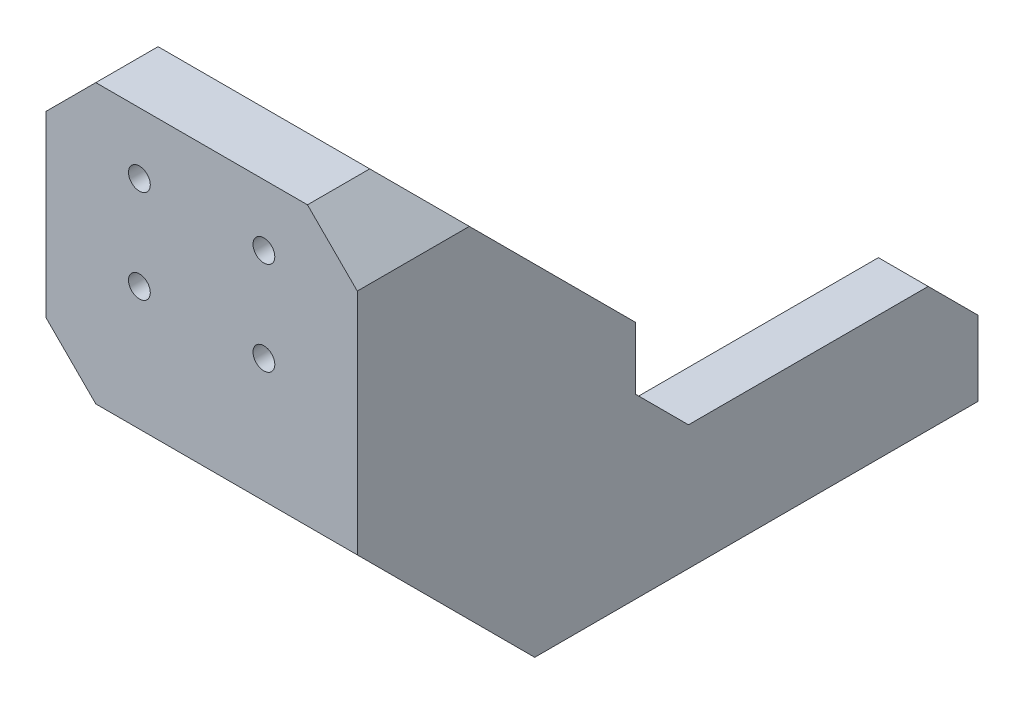
SolidWorks part; units mm, degrees
ref_plane "Front Plane" through (0, 0, 0) normal (0, 0, 1) x (1, 0, 0)
ref_plane "Top Plane" through (0, 0, 0) normal (0, 1, 0) x (1, 0, 0)
ref_plane "Right Plane" through (0, 0, 0) normal (1, 0, 0) x (0, 0, -1)
sketch "Sketch1" plane through (0, 0, 0) normal (0, 1, 0) x (1, 0, 0)
  line L1 (-25, -17.35) -> (25, -17.35)
  line L2 (-25, -17.35) -> (-25, 17.35)
  line L3 (-25, 17.35) -> (25, 17.35)
  line L4 (25, -17.35) -> (25, 17.35)
  line L5 (-25, -17.35) -> (25, 17.35) construction
  line L6 (-25, 17.35) -> (25, -17.35) construction
  point P0 (0, 0)
  dimension "D1" = 50
  dimension "D2" = 34.7
extrude "Boss-Extrude1" add sketch "Sketch1" along normal blind 10
sketch "Sketch2" plane through (0, 10, 0) normal (0, 1, 0) x (1, 0, 0)
  line L1 (-10, -7.5) -> (10, -7.5) construction
  line L2 (-10, -7.5) -> (-10, 7.5) construction
  line L3 (-10, 7.5) -> (10, 7.5) construction
  line L4 (10, -7.5) -> (10, 7.5) construction
  line L5 (-10, -7.5) -> (10, 7.5) construction
  line L6 (-10, 7.5) -> (10, -7.5) construction
  circle A0 centre (-10, 7.5) radius 1.75
  circle A1 centre (10, 7.5) radius 1.75
  circle A2 centre (10, -7.5) radius 1.75
  circle A3 centre (-10, -7.5) radius 1.75
  point P0 (0, 0)
  dimension "D1" = 3.5
  dimension "D2" = 20
  dimension "D3" = 15
extrude "Cut-Extrude1" cut sketch "Sketch2" against normal up to next
sketch "Sketch3" plane through (0, 10, 0) normal (0, 1, 0) x (1, 0, 0)
  circle A3 centre (-10, 7.5) radius 3
  circle A4 centre (10, 7.5) radius 3
  circle A5 centre (10, -7.5) radius 3
  circle A6 centre (-10, -7.5) radius 3
  dimension "D1" = 6
extrude "Cut-Extrude2" cut sketch "Sketch3" against normal blind 5
sketch "Sketch6" plane through (0, 0, 0) normal (0, -1, 0) x (1, 0, 0)
  line L0 (25, 17.35) -> (25, -17.35) construction
  line L1 (-25, 17.35) -> (25, 17.35)
  line L2 (-25, 17.35) -> (-25, 27.35)
  line L3 (-25, 27.35) -> (25, 27.35)
  line L4 (25, 17.35) -> (25, 27.35)
  dimension "D1" = 10
extrude "Boss-Extrude3" add sketch "Sketch6" against normal blind 44.7
sketch "Sketch8" plane through (25, 0, 0) normal (1, 0, 0) x (0, 0, -1)
  line L0 (-27.35, 0) -> (17.35, 0)
  line L1 (-27.35, 0) -> (17.35, 0) construction
  line L2 (17.35, 0) -> (25.85, -8.5)
  line L3 (25.85, -8.5) -> (72.35, -8.5)
  line L4 (72.35, -8.5) -> (72.35, -28.5)
  line L5 (72.35, -28.5) -> (1.15, -28.5)
  line L6 (1.15, -28.5) -> (-27.35, 0)
  line L7 (17.35, 10) -> (17.35, 0) construction
  point P11 (0, 0)
  dimension "D1" = 28.5
  dimension "D2" = 20
  dimension "D3" = 45
  dimension "D4" = 55
extrude "Boss-Extrude4" add sketch "Sketch8" against normal blind 8
sketch "Sketch9" plane through (25, 0, 0) normal (1, 0, 0) x (0, 0, -1)
  line L0 (-17.35, 44.7) -> (17.35, 10)
  line L1 (17.35, 10) -> (-17.35, 10)
  line L2 (-17.35, 10) -> (-17.35, 44.7)
extrude "Boss-Extrude5" add sketch "Sketch9" against normal blind 8
chamfer "Chamfer1" distance 8 angle 45 1 edges at (21, -8.5, -72.35)
mirror "Mirror1" about plane through (0, 0, 0) normal (1, 0, 0) of "Boss-Extrude5"
sketch "Sketch10" plane through (0, 0, 17.35) normal (0, 0, -1) x (-1, 0, 0)
  line L0 (17, 27.35) -> (0, 27.35) construction
  line L1 (17, 44.7) -> (17, 10) construction
  line L2 (0, 27.35) -> (0, 10) construction
  line L3 (-17, 10) -> (17, 10) construction
  line L5 (10, 19.85) -> (-10, 19.85) construction
  line L6 (10, 19.85) -> (10, 34.85) construction
  line L7 (10, 34.85) -> (-10, 34.85) construction
  line L8 (-10, 19.85) -> (-10, 34.85) construction
  line L9 (10, 19.85) -> (-10, 34.85) construction
  line L10 (10, 34.85) -> (-10, 19.85) construction
  circle A0 centre (-10, 34.85) radius 1.75
  circle A1 centre (10, 34.85) radius 1.75
  circle A2 centre (10, 19.85) radius 1.75
  circle A3 centre (-10, 19.85) radius 1.75
  dimension "D1" = 3.5
  dimension "D2" = 15
  dimension "D3" = 20
extrude "Cut-Extrude3" cut sketch "Sketch10" against normal up to next
chamfer "Chamfer2" distance 8 angle 45 3 edges at (25, 44.7, 22.35) (-25, 44.7, 22.35) (-25, 0, 5)
